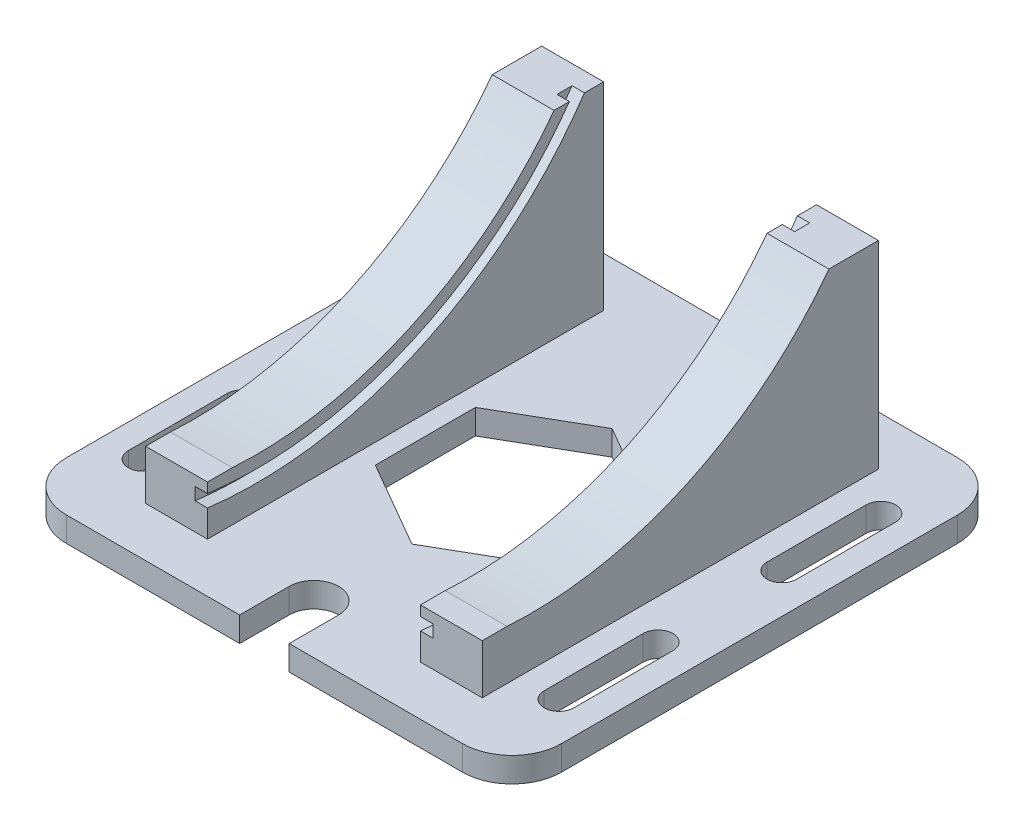
SolidWorks part; units mm, degrees
ref_plane "Alzado" through (0, 0, 0) normal (0, 0, 1) x (1, 0, 0)
ref_plane "Planta" through (0, 0, 0) normal (0, 1, 0) x (1, 0, 0)
ref_plane "Vista lateral" through (0, 0, 0) normal (1, 0, 0) x (0, 0, -1)
sketch "Croquis2" plane through (0, 0, 0) normal (0, 1, 0) x (1, 0, 0)
  line L1 (50, -50) -> (-50, -50)
  line L2 (50, -50) -> (50, 50)
  line L3 (50, 50) -> (-50, 50)
  line L4 (-50, -50) -> (-50, 50)
  line L5 (50, -50) -> (-50, 50) construction
  line L6 (50, 50) -> (-50, -50) construction
  point P0 (0, 0)
  dimension "D1" = 100
  dimension "D2" = 100
extrude "Saliente-Extruir1" add sketch "Croquis2" along normal blind 5
fillet "Redondeo1" radius 10 4 edges at (-50, 2.5, -50) (50, 2.5, -50) (-50, 2.5, 50) (50, 2.5, 50)
sketch "Croquis3" plane through (0, 5, 0) normal (0, 1, 0) x (1, 0, 0)
  line L0 (-40, -50) -> (40, -50) construction
  line L1 (-5, -50) -> (5, -50)
  line L2 (-5, -50) -> (-5, -40)
  line L4 (5, -50) -> (5, -40)
  line L5 (-42, 32.5) -> (-42, 12.5) construction
  line L6 (-39, 32.5) -> (-39, 12.5)
  line L7 (-45, 32.5) -> (-45, 12.5)
  line L8 (42, 32.5) -> (42, 12.5) construction
  line L9 (45, 32.5) -> (45, 12.5)
  line L10 (39, 32.5) -> (39, 12.5)
  line L11 (-42, -12.5) -> (-42, -32.5) construction
  line L12 (-39, -12.5) -> (-39, -32.5)
  line L13 (-45, -12.5) -> (-45, -32.5)
  line L14 (42, -12.5) -> (42, -32.5) construction
  line L15 (45, -12.5) -> (45, -32.5)
  line L16 (39, -12.5) -> (39, -32.5)
  line L18 (-50, 40) -> (-50, -40) construction
  line L19 (50, -40) -> (50, 40) construction
  line L20 (0, 20.2073) -> (-17.5, 10.1036)
  line L21 (-17.5, 10.1036) -> (-17.5, -10.1036)
  line L22 (-17.5, -10.1036) -> (0, -20.2073)
  line L23 (0, -20.2073) -> (17.5, -10.1036)
  line L24 (17.5, -10.1036) -> (17.5, 10.1036)
  line L25 (17.5, 10.1036) -> (0, 20.2073)
  arc A0 (5, -40) -> (-5, -40) centre (0, -40) ccw
  arc A1 (-39, 32.5) -> (-45, 32.5) centre (-42, 32.5) ccw
  arc A2 (-45, 12.5) -> (-39, 12.5) centre (-42, 12.5) ccw
  arc A3 (45, 32.5) -> (39, 32.5) centre (42, 32.5) ccw
  arc A4 (39, 12.5) -> (45, 12.5) centre (42, 12.5) ccw
  arc A5 (-39, -12.5) -> (-45, -12.5) centre (-42, -12.5) ccw
  arc A6 (-45, -32.5) -> (-39, -32.5) centre (-42, -32.5) ccw
  arc A7 (45, -12.5) -> (39, -12.5) centre (42, -12.5) ccw
  arc A8 (39, -32.5) -> (45, -32.5) centre (42, -32.5) ccw
  circle A9 centre (0, 0) radius 17.5 construction
  point P10 (-42, 22.5)
  point P15 (42, 22.5)
  point P22 (-42, -22.5)
  point P29 (42, -22.5)
  point P37 (0, 0)
  dimension "D2" = 5
  dimension "D5" = 3
  dimension "D10" = 35
  dimension "D1" = 10
  dimension "D3" = 22.5
  dimension "D4" = 5
  dimension "D6" = 20
  dimension "D7" = 5
  dimension "D8" = 45
  dimension "D9" = 20
extrude "Cortar-Extruir1" cut sketch "Croquis3" against normal blind 5
sketch "Croquis4" plane through (0, 5, 0) normal (0, 1, 0) x (1, 0, 0)
  line L0 (-39, 12.5) -> (-39, 32.5) construction
  line L1 (-34, 40) -> (-24, 40)
  line L2 (-34, 40) -> (-34, -40)
  line L3 (-34, -40) -> (-24, -40)
  line L4 (-24, 40) -> (-24, -40)
  line L5 (24, 40) -> (34, 40)
  line L6 (24, 40) -> (24, -40)
  line L7 (24, -40) -> (34, -40)
  line L8 (34, 40) -> (34, -40)
  line L9 (39, 32.5) -> (39, 12.5) construction
  point P8 (-24, 0)
  point P10 (24, 0)
  point P15 (0, 0)
  dimension "D1" = 10
  dimension "D2" = 10
  dimension "D3" = 5
  dimension "D4" = 5
  dimension "D5" = 80
extrude "Saliente-Extruir2" add sketch "Croquis4" along normal blind 40
sketch "Croquis5" plane through (34, 0, 0) normal (1, 0, 0) x (0, 0, -1)
  line L1 (-40, 5) -> (40, 5) construction
  line L5 (-40, 15) -> (-35, 15)
  line L7 (-40, 45) -> (40, 45) construction
  line L8 (-40, 15) -> (-40, 45)
  line L9 (-40, 45) -> (30, 45)
  line L11 (40, 45) -> (40, 5) construction
  arc A0 (-35, 15) -> (30, 45) centre (-30.1189, 89.841) ccw
  dimension "D4" = 75
  dimension "D1" = 10
  dimension "D2" = 5
  dimension "D3" = 10
extrude "Cortar-Extruir2" cut sketch "Croquis5" against normal blind 84
sketch "Croquis8" plane through (-24, 0, 0) normal (1, 0, 0) x (0, 0, -1)
  line L0 (30, 45) -> (40, 45) construction
  line L1 (-40, 15) -> (-40, 5) construction
  line L2 (-40, 12.9735) -> (-40, 15)
  line L3 (33.0913, 45) -> (30, 45)
  line L5 (-40, 15) -> (-35, 15)
  arc A1 (-35, 15) -> (30, 45) centre (-30.1189, 89.841) ccw construction
  arc A2 (-35.1627, 12.5053) -> (32.004, 43.5053) centre (-30.1189, 89.841) ccw
  arc A3 (-40, 12.9735) -> (33.0913, 45) centre (-30.1189, 89.841) ccw
  arc A4 (-35, 15) -> (30, 45) centre (-30.1189, 89.841) ccw
  dimension "D1" = 2.5
extrude "Saliente-Extruir4" add sketch "Croquis8" along normal blind 2.5
sketch "Croquis9" plane through (-24, 0, 0) normal (1, 0, 0) x (0, 0, -1)
  line L1 (33.0913, 45) -> (40, 45) construction
  line L2 (-40, 12.9735) -> (-40, 5) construction
  line L3 (-40, 10.4536) -> (-40, 5)
  line L4 (-40, 5) -> (40, 5)
  line L5 (40, 5) -> (40, 45)
  line L6 (40, 45) -> (36.1328, 45)
  arc A2 (-40.3187, 10.4939) -> (35.1304, 43.5535) centre (-30.1189, 89.841) ccw
  arc A3 (-40, 10.4536) -> (36.1328, 45) centre (-30.1189, 89.841) ccw
  dimension "D1" = 2.5
extrude "Saliente-Extruir5" add sketch "Croquis9" along normal blind 2.5
mirror "Simetría1" about plane through (0, 0, 0) normal (1, 0, 0) of "Saliente-Extruir4", "Saliente-Extruir5"
